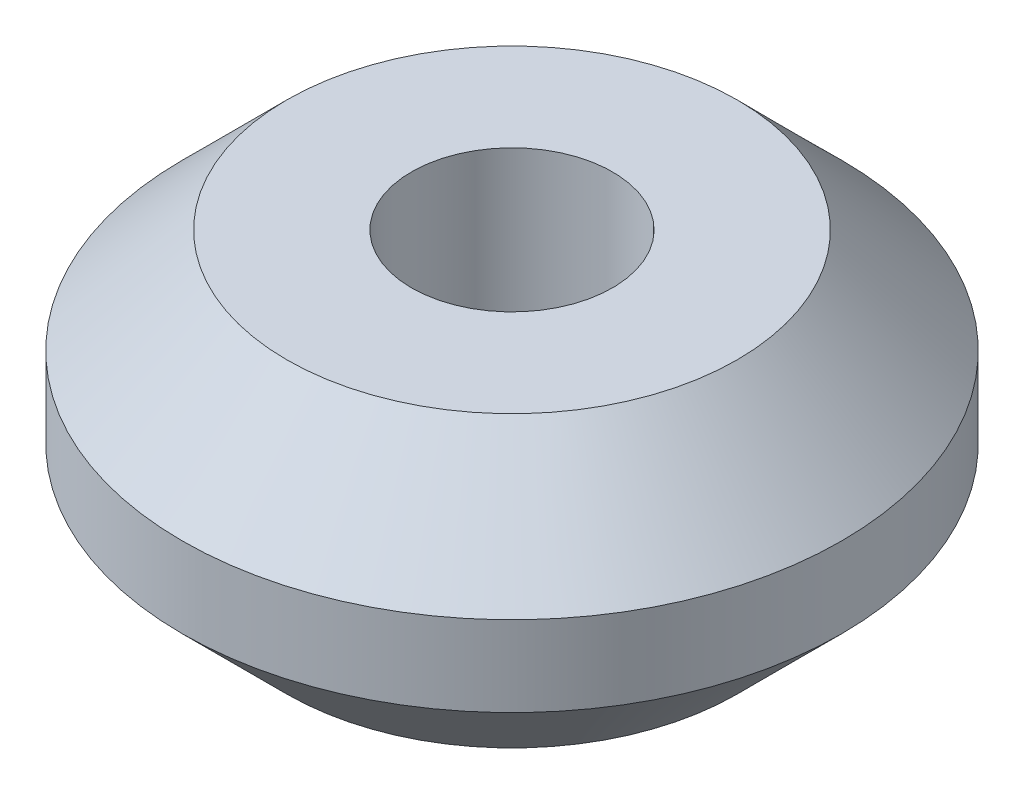
SolidWorks part; units mm, degrees
material "NEOPRENE"
ref_plane "Front Plane" through (0, 0, 0) normal (0, 0, 1) x (1, 0, 0)
ref_plane "Top Plane" through (0, 0, 0) normal (0, 1, 0) x (1, 0, 0)
ref_plane "Right Plane" through (0, 0, 0) normal (1, 0, 0) x (0, 0, -1)
sketch "Sketch1" plane through (0, 0, 0) normal (0, 1, 0) x (1, 0, 0)
  circle A0 centre (0, 0) radius 20.5
  dimension "D1" = 41
extrude "Boss-Extrude1" add sketch "Sketch1" along normal blind 18
chamfer "Chamfer1" distance 6.5 angle 45 2 edges at (0, 18, 20.5) (0, 0, 20.5)
sketch "Sketch2" plane through (0, 18, 0) normal (0, 1, 0) x (1, 0, 0)
  circle A0 centre (0, 0) radius 6.25
  dimension "D1" = 12.5
extrude "Cut-Extrude1" cut sketch "Sketch2" against normal through all
